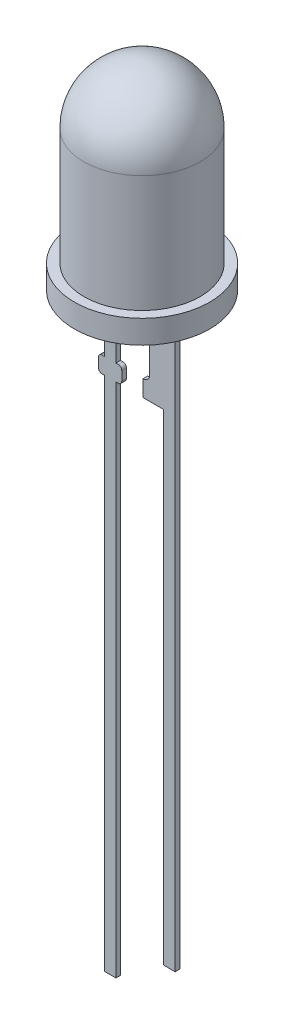
SolidWorks part; units mm, degrees
ref_plane "Alzado" through (0, 0, 0) normal (0, 0, 1) x (1, 0, 0)
ref_plane "Planta" through (0, 0, 0) normal (0, 1, 0) x (1, 0, 0)
ref_plane "Vista lateral" through (0, 0, 0) normal (1, 0, 0) x (0, 0, -1)
sketch "Croquis1" plane through (0, 0, 0) normal (0, 0, 1) x (1, 0, 0)
  line L0 (2.1412, -3.597) -> (1.2612, -3.597)
  line L2 (-0.3988, 0.2745) -> (-0.3988, -2.897)
  line L3 (-0.3988, -25.7255) -> (0.1012, -25.7255)
  line L4 (0.1012, 0.2745) -> (0.1012, -2.897)
  line L6 (2.1412, -3.597) -> (2.1412, -24.2255)
  line L7 (2.1412, -24.2255) -> (2.6412, -24.2255)
  line L8 (2.6412, 0.2745) -> (2.6412, -24.2255)
  line L9 (1.2612, -3.597) -> (1.2612, -2.897)
  line L11 (1.5475, 0.2745) -> (1.5475, -2.617)
  line L12 (1.2675, -2.897) -> (1.2612, -2.897)
  line L13 (0.1012, -2.897) -> (0.2012, -2.897)
  line L14 (-0.4988, -2.897) -> (-0.3988, -2.897)
  line L15 (-0.6488, -3.047) -> (-0.6488, -3.447)
  line L16 (-0.4988, -3.597) -> (-0.3988, -3.597)
  line L17 (0.3512, -3.047) -> (0.3512, -3.447)
  line L18 (-0.3988, -3.597) -> (-0.3988, -25.7255)
  line L19 (0.1012, -3.597) -> (0.1012, -25.7255)
  line L20 (0.1012, -3.597) -> (0.2012, -3.597)
  line L21 (1.5475, 0.2745) -> (1.5475, 1.4618)
  line L22 (1.5475, 1.4618) -> (0.6412, 1.9745)
  line L23 (0.6412, 1.9745) -> (0.6412, 4.7745)
  line L24 (2.6412, 0.2745) -> (2.6412, 1.4618)
  line L25 (0.1012, 0.2745) -> (0.1012, 4.7745)
  line L26 (0.1012, 4.7745) -> (-0.3988, 4.7745)
  line L27 (-0.8988, 0.946) -> (-0.8988, 0.2745)
  line L28 (-0.3988, 0.2745) -> (-0.8988, 0.2745)
  line L29 (0.6412, 4.7745) -> (2.8412, 4.7745)
  line L30 (-0.3988, 4.7745) -> (-0.3988, 2.0562)
  line L31 (-0.3988, 2.0562) -> (-0.8988, 0.946)
  line L32 (2.6412, 1.4618) -> (2.8412, 1.4618)
  line L33 (2.8412, 1.4618) -> (2.8412, 4.7745)
  arc A0 (1.5475, -2.617) -> (1.2675, -2.897) centre (1.2675, -2.617) cw
  arc A1 (-0.6488, -3.447) -> (-0.4988, -3.597) centre (-0.4988, -3.447) ccw
  arc A2 (0.2012, -3.597) -> (0.3512, -3.447) centre (0.2012, -3.447) ccw
  arc A3 (0.2012, -2.897) -> (0.3512, -3.047) centre (0.2012, -3.047) cw
  arc A4 (-0.6488, -3.047) -> (-0.4988, -2.897) centre (-0.4988, -3.047) cw
  point P8 (-0.1488, -25.7255)
  point P9 (2.3912, -24.2255)
  point P30 (0.3512, -2.897)
  point P33 (-0.6488, -2.897)
extrude "Saliente-Extruir1" add sketch "Croquis1" along normal mid plane 0.2
ref_plane "Plano1" through (0, 0.2745, 0) normal (0, -1, 0) x (-1, 0, 0)
ref_plane "Plano2" through (0, -25.7255, 0) normal (0, -1, 0) x (-1, 0, 0)
sketch "Croquis5" plane through (0, -25.7255, 0) normal (0, -1, 0) x (-1, 0, 0)
  line L0 (-0.1012, 0) -> (-2.1412, 0) construction
  line L1 (-0.1012, -0.1) -> (-0.1012, 0.1) construction
  line L2 (-1.1212, -1.02) -> (-1.1212, 1.02) construction
  circle A0 centre (-1.1212, 0) radius 1.02
  point P8 (-1.1212, 0)
sketch "Croquis7" plane through (0, 0.2745, 0) normal (0, -1, 0) x (-1, 0, 0)
  line L0 (-0.1012, 0) -> (-2.1412, 0) construction
  circle A0 centre (-1.1212, 0) radius 2.9
  dimension "D1" = 5.8
extrude "Saliente-Extruir2" add sketch "Croquis7" against normal blind 1
sketch "Croquis9" plane through (0, 0, 0) normal (0, 0, 1) x (1, 0, 0)
  line L0 (-1.3708, 1.2745) -> (-1.3708, 6.2794)
  line L1 (4.0212, 1.2745) -> (-1.7788, 1.2745) construction
  line L2 (1.1212, 8.6814) -> (1.1212, 8.7794)
  line L3 (-1.3708, 1.2745) -> (-1.2708, 1.2745)
  line L4 (-1.7788, 1.2745) -> (-1.7788, 0.2745) construction
  line L5 (1.0212, 8.6769) -> (1.1212, 8.6814)
  line L6 (-1.2708, 1.3745) -> (-1.2708, 6.2794) construction
  line L7 (-1.3708, 1.2745) -> (1.1212, 1.2745) construction
  line L8 (1.1212, 8.7794) -> (1.1212, 8.6814) construction
  line L9 (-1.2708, 1.2745) -> (-1.2708, 6.2794)
  line L12 (1.0212, 1.3745) -> (1.0212, 8.6769) construction
  line L13 (-1.2708, 1.3745) -> (1.0212, 1.3745) construction
  line L14 (1.1212, 1.2745) -> (1.1212, 8.7794) construction
  line L15 (1.1212, 8.6814) -> (1.1212, 5.3177) construction
  arc A0 (1.1212, 8.7794) -> (-1.3708, 6.2794) centre (1.1292, 6.2794) ccw
  arc A1 (1.0212, 8.6769) -> (-1.2708, 6.2794) centre (1.1292, 6.2794) ccw
  dimension "D1" = 0.408
  dimension "D2" = 0.1
revolve "Revolución2" add sketch "Croquis9" angle 360 about L15
